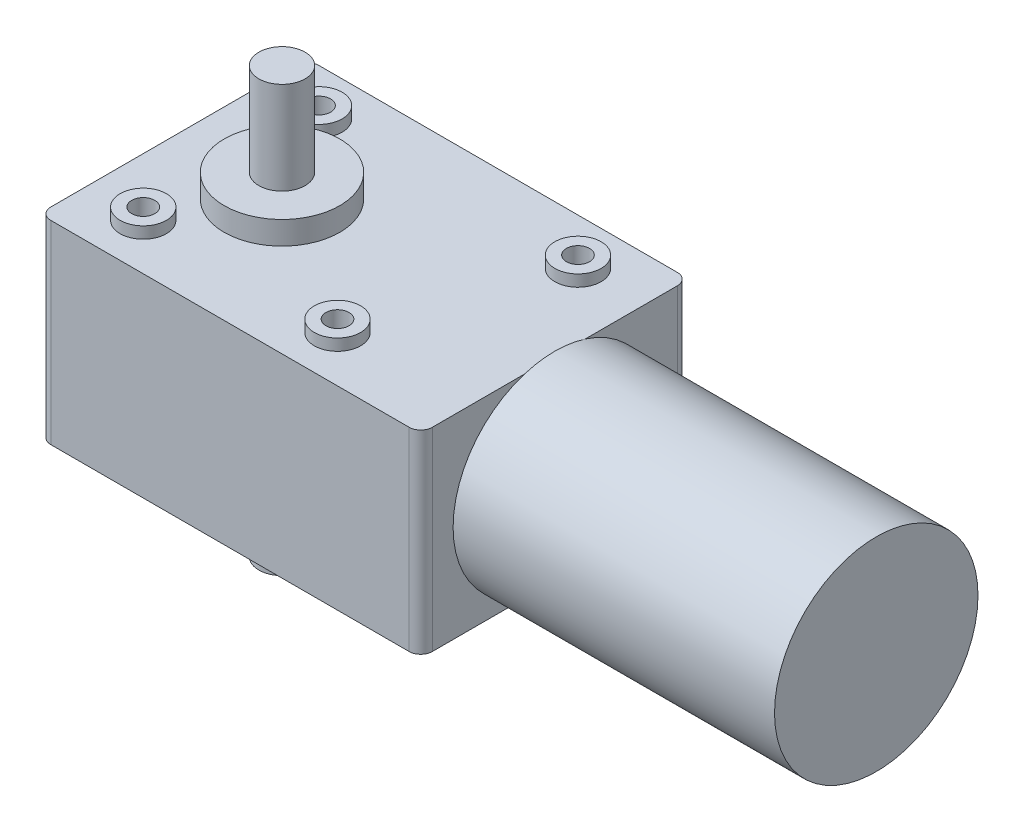
SolidWorks part; units mm, degrees
ref_plane "Front Plane" through (0, 0, 0) normal (0, 0, 1) x (1, 0, 0)
ref_plane "Top Plane" through (0, 0, 0) normal (0, 1, 0) x (1, 0, 0)
ref_plane "Right Plane" through (0, 0, 0) normal (1, 0, 0) x (0, 0, -1)
sketch "Sketch1" plane through (0, 0, 0) normal (0, 1, 0) x (1, 0, 0)
  line L1 (-38.75, -29) -> (38.75, -29)
  line L2 (-41.25, -26.5) -> (-41.25, 26.5)
  line L3 (-38.75, 29) -> (38.75, 29)
  line L4 (41.25, -26.5) -> (41.25, 26.5)
  line L5 (-41.25, -29) -> (41.25, 29) construction
  line L6 (-41.25, 29) -> (41.25, -29) construction
  arc A0 (-41.25, -26.5) -> (-38.75, -29) centre (-38.75, -26.5) ccw
  arc A1 (38.75, -29) -> (41.25, -26.5) centre (38.75, -26.5) ccw
  arc A2 (41.25, 26.5) -> (38.75, 29) centre (38.75, 26.5) ccw
  arc A3 (-41.25, 26.5) -> (-38.75, 29) centre (-38.75, 26.5) cw
  point P0 (0, 0)
  dimension "D3" = 2.5
  dimension "D1" = 82.5
  dimension "D2" = 58
extrude "Boss-Extrude1" add sketch "Sketch1" along normal mid plane 42
sketch "Sketch2" plane through (0, 21, 0) normal (0, 1, 0) x (1, 0, 0)
  line L0 (-1000, 0) -> (49000, 0) construction
  line L1 (-1000.4558, 19) -> (48999.5442, 19) construction
  line L2 (-1000.9116, -19) -> (48999.0884, -19) construction
  line L3 (-28.75, -994.0746) -> (-28.75, 49005.9254) construction
  line L4 (27.25, -995.2141) -> (27.25, 49004.7859) construction
  line L5 (-41.25, 26.5) -> (-41.25, -26.5) construction
  line L6 (13.25, -1014) -> (13.25, 48986) construction
  circle A0 centre (-28.75, 19) radius 5
  circle A1 centre (-28.75, -19) radius 5
  circle A2 centre (13.25, -19) radius 5
  circle A3 centre (27.25, 19) radius 5
  dimension "D5" = 10
  dimension "D6" = 10
  dimension "D7" = 10
  dimension "D8" = 10
  dimension "D9" = 42
  dimension "D1" = 19
  dimension "D2" = 19
  dimension "D3" = 12.5
  dimension "D4" = 56
extrude "Boss-Extrude2" add sketch "Sketch2" along normal blind 2.5
sketch "Sketch3" plane through (0, 23.5, 0) normal (0, 1, 0) x (1, 0, 0)
  circle A0 centre (-28.75, 19) radius 2.5
  circle A1 centre (27.25, 19) radius 2.5
  circle A2 centre (13.25, -19) radius 2.5
  circle A3 centre (-28.75, -19) radius 2.5
  dimension "D1" = 5
  dimension "D2" = 5
  dimension "D3" = 5
  dimension "D4" = 5
extrude "Cut-Extrude1" cut sketch "Sketch3" against normal blind 6
sketch "Sketch6" plane through (0, 21, 0) normal (0, 1, 0) x (1, 0, 0)
  line L0 (-1000, 0) -> (49000, 0) construction
  line L1 (-41.25, 26.5) -> (-41.25, -26.5) construction
  circle A0 centre (-17.75, 0) radius 12.5
  dimension "D1" = 25
  dimension "D2" = 23.5
extrude "Boss-Extrude5" add sketch "Sketch6" along normal blind 5
sketch "Sketch4" plane through (0, 26, 0) normal (0, 1, 0) x (1, 0, 0)
  circle A0 centre (-17.75, 0) radius 5
  circle A1 centre (-17.75, 0) radius 12.5 construction
  dimension "D1" = 10
extrude "Boss-Extrude3" add sketch "Sketch4" along normal blind 20
sketch "Sketch5" plane through (41.25, 0, 0) normal (1, 0, 0) x (0, 0, -1)
  line L1 (0, -1000) -> (0, 49000) construction
  circle A0 centre (0, 0) radius 22
  dimension "D2" = 44
extrude "Boss-Extrude4" add sketch "Sketch5" along normal blind 69.5
mirror "Mirror2" about plane through (0, 0, 0) normal (0, 1, 0) of "Boss-Extrude3", "Boss-Extrude2", "Cut-Extrude1", "Boss-Extrude5"
